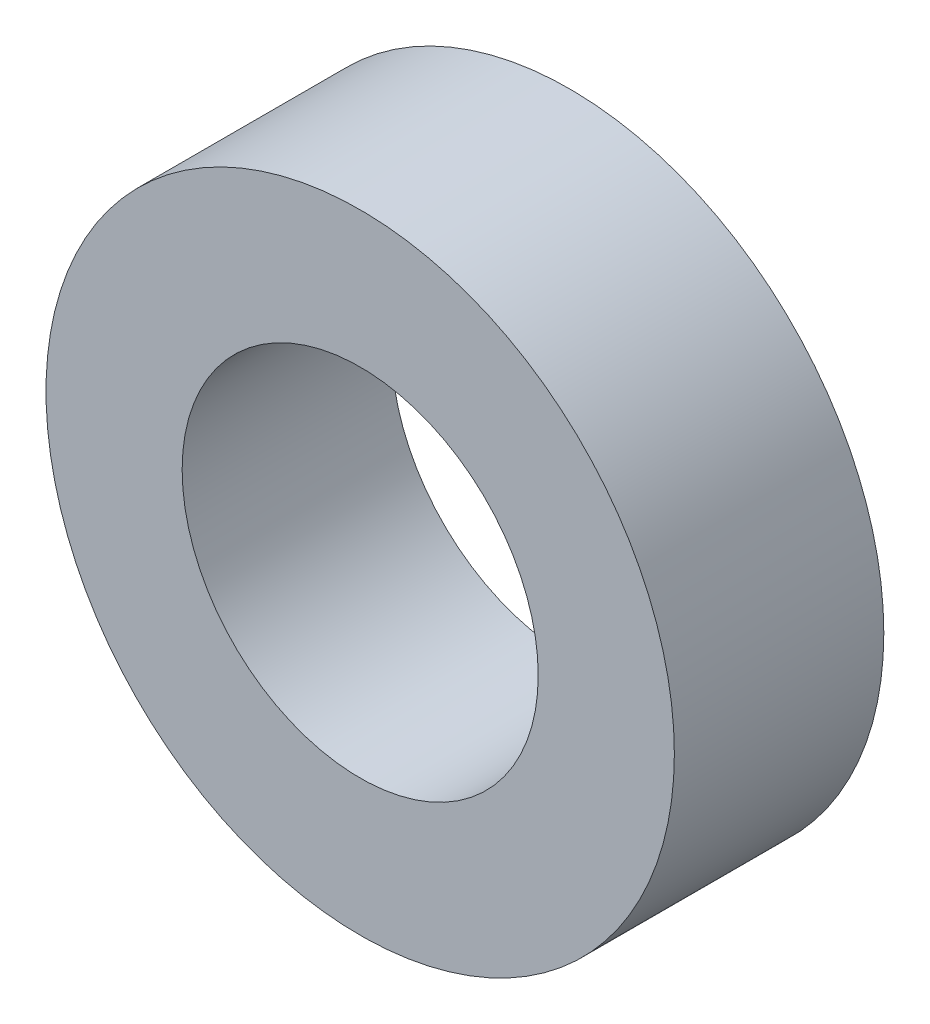
SolidWorks part; units mm, degrees
other "Pico Controller Mount 1 Standoff"
ref_plane "Front Plane" through (0, 0, 0) normal (0, 0, 1) x (1, 0, 0)
ref_plane "Top Plane" through (0, 0, 0) normal (0, 1, 0) x (1, 0, 0)
ref_plane "Right Plane" through (0, 0, 0) normal (1, 0, 0) x (0, 0, -1)
sketch3d "Main Profile Sketch datum points"
  point P0 (0, 0, 71)
  point P1 (10, 0, 71)
  point P2 (0, 10, 71)
ref_plane "Main Profile Sketch plane" through (0, 0, 71) normal (0, 0, 1) x (1, 0, 0)
sketch "Main Profile Sketch" plane through (0, 0, 71) normal (0, 0, 1) x (1, 0, 0)
  circle A0 centre (-147, 33) radius 3
  circle A1 centre (-147, 33) radius 1.7
extrude "Main Extrusion" add sketch "Main Profile Sketch" against normal blind 2 separate body
